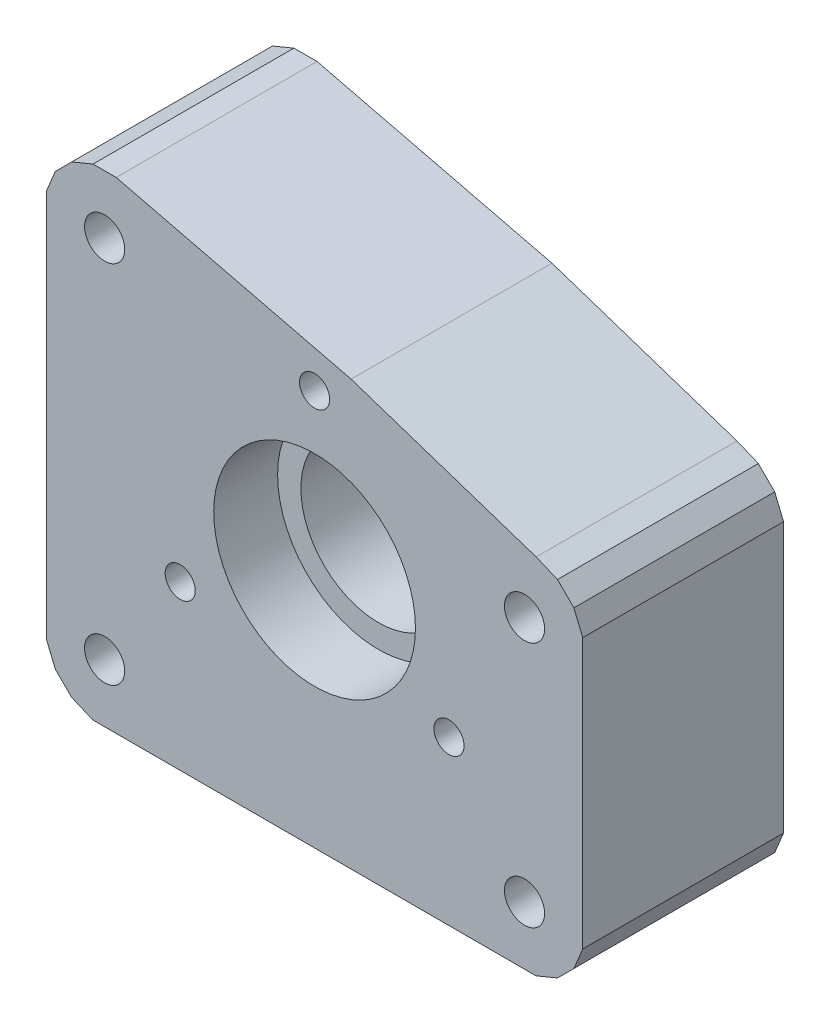
SolidWorks part; units mm, degrees
ref_plane "前视基准面" through (0, 0, 0) normal (0, 0, 1) x (1, 0, 0)
ref_plane "上视基准面" through (0, 0, 0) normal (0, 1, 0) x (1, 0, 0)
ref_plane "右视基准面" through (0, 0, 0) normal (1, 0, 0) x (0, 0, -1)
other "Configuration Table"
sketch "Profile_1" plane through (0, 0, 0) normal (0, 0, 1) x (1, 0, 0)
  line L0 (26.6112, -25.4046) -> (28.4046, -23.6112)
  line L1 (28.4046, -23.6112) -> (29.3751, -21.2681)
  line L2 (29.3751, -21.2681) -> (29.3751, 8.2681)
  line L3 (29.3751, 8.2681) -> (28.4046, 10.6112)
  line L4 (28.4046, 10.6112) -> (26.6112, 12.4046)
  line L5 (26.6112, 12.4046) -> (24.2681, 13.3751)
  line L6 (24.2681, 13.3751) -> (3.9994, 20.1061)
  line L7 (3.9994, 20.1061) -> (-21.7319, 26.3751)
  line L8 (-21.7319, 26.3751) -> (-24.2681, 26.3751)
  line L9 (-24.2681, 26.3751) -> (-26.6112, 25.4046)
  line L10 (-26.6112, 25.4046) -> (-28.4046, 23.6112)
  line L11 (-28.4046, 23.6112) -> (-29.3751, 21.2681)
  line L12 (-29.3751, 21.2681) -> (-29.3751, -21.2681)
  line L13 (-29.3751, -21.2681) -> (-28.4046, -23.6112)
  line L14 (-28.4046, -23.6112) -> (-26.6112, -25.4046)
  line L15 (-26.6112, -25.4046) -> (-24.2681, -26.3751)
  line L16 (-24.2681, -26.3751) -> (24.2681, -26.3751)
  line L17 (24.2681, -26.3751) -> (26.6112, -25.4046)
  circle A0 centre (0, 0) radius 8.5
  circle A1 centre (23, -20) radius 2.2
  circle A2 centre (-23, -20) radius 2.2
  circle A3 centre (23, 7) radius 2.2
  circle A4 centre (-23, 20) radius 2.2
  circle A5 centre (0, 17) radius 1.65
  circle A6 centre (14.7224, -8.5) radius 1.65
  circle A7 centre (-14.7224, -8.5) radius 1.65
extrude "Cartridge_body" add sketch "Profile_1" along normal blind 22 from offset 34
sketch "Profile_2" plane through (0, 0, 0) normal (0, 0, 1) x (1, 0, 0)
  circle A0 centre (0, 0) radius 11.05
extrude "Inboard_608_seat" cut sketch "Profile_2" along normal blind 7.01 from offset 33.99
sketch "Profile_3" plane through (0, 0, 0) normal (0, 0, 1) x (1, 0, 0)
  circle A0 centre (0, 0) radius 11.05
extrude "Outboard_608_seat" cut sketch "Profile_3" along normal blind 7.01 from offset 49
